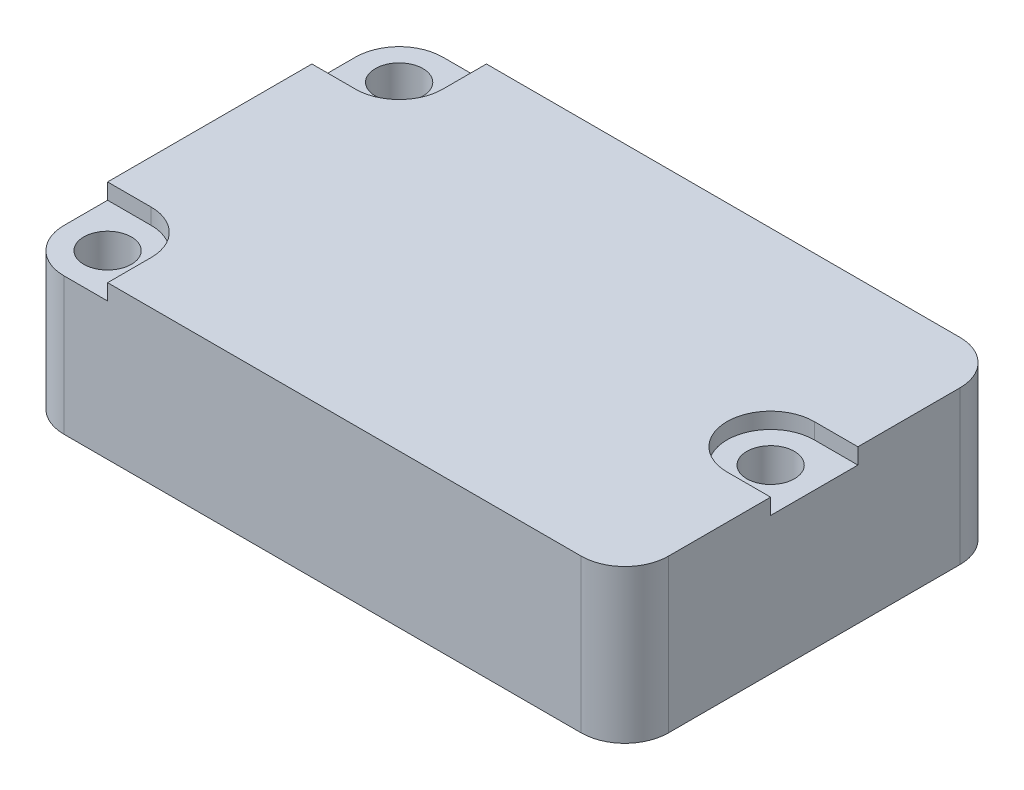
SolidWorks part; units mm, degrees
ref_plane "Front Plane" through (0, 0, 0) normal (0, 0, 1) x (1, 0, 0)
ref_plane "Top Plane" through (0, 0, 0) normal (0, 1, 0) x (1, 0, 0)
ref_plane "Right Plane" through (0, 0, 0) normal (1, 0, 0) x (0, 0, -1)
sketch "Sketch1" plane through (0, 0, 0) normal (0, 1, 0) x (1, 0, 0)
  line L0 (35.35, -2.75) -> (35.35, -21.126) construction
  line L1 (2.75, 0) -> (35.35, 0)
  line L2 (0, -2.75) -> (0, -21.126)
  line L3 (2.75, -23.876) -> (35.35, -23.876)
  line L4 (38.1, -2.75) -> (38.1, -21.126)
  arc A0 (35.35, 0) -> (38.1, -2.75) centre (35.35, -2.75) cw
  arc A1 (35.35, -23.876) -> (38.1, -21.126) centre (35.35, -21.126) ccw
  arc A2 (0, -21.126) -> (2.75, -23.876) centre (2.75, -21.126) ccw
  arc A3 (2.75, 0) -> (0, -2.75) centre (2.75, -2.75) ccw
  circle A4 centre (2.75, -2.75) radius 1.5
  circle A7 centre (2.75, -21.126) radius 1.5
  circle A8 centre (35.35, -11.938) radius 1.5
  point P9 (38.1, -23.876)
  point P12 (0, -23.876)
  point P15 (0, 0)
  dimension "D3" = 2.75
  dimension "D4" = 3
  dimension "D5" = 3
  dimension "D6" = 3
  dimension "D1" = 23.876
  dimension "D2" = 38.1
extrude "Boss-Extrude1" add sketch "Sketch1" along normal blind 9.65
sketch "Sketch2" plane through (0, 9.65, 0) normal (0, 1, 0) x (1, 0, 0)
  line L4 (5.5, -5.5) -> (0, -5.5)
  line L6 (5.5, -5.5) -> (5.5, 0)
  line L7 (5.5, 0) -> (0, 0)
  line L8 (0, -5.5) -> (0, 0)
  line L9 (5.5, -18.376) -> (0, -18.376)
  line L10 (5.5, -18.376) -> (5.5, -23.876)
  line L11 (38.1, -21.126) -> (38.1, -2.75) construction
  line L12 (35.35, -9.188) -> (38.1, -9.188)
  line L13 (35.35, -9.188) -> (35.35, -14.688)
  line L14 (35.35, -14.688) -> (38.1, -14.688)
  line L15 (38.1, -9.188) -> (38.1, -14.688)
  line L16 (5.5, -23.876) -> (0, -23.876)
  line L17 (0, -18.376) -> (0, -23.876)
  circle A0 centre (2.75, -2.75) radius 2.75
  circle A1 centre (2.75, -21.126) radius 2.75
  circle A2 centre (35.35, -11.938) radius 2.75
  line M25 (35.35, 0) -> (2.75, 0)
  arc M26 (2.75, 0) -> (0, -2.75) centre (2.75, -2.75) ccw
  line M27 (0, -2.75) -> (0, -21.126)
  arc M28 (0, -21.126) -> (2.75, -23.876) centre (2.75, -21.126) ccw
  line M29 (2.75, -23.876) -> (35.35, -23.876)
  line M31 (38.1, -21.126) -> (38.1, -2.75)
  circle M32 centre (2.75, -2.75) radius 1.5
  circle M33 centre (35.35, -11.938) radius 1.5
  circle M34 centre (2.75, -21.126) radius 1.5
  dimension "D1" = 5.5
  dimension "D2" = 5.5
  dimension "D3" = 5.5
extrude "Cut-Extrude1" cut sketch "Sketch2" against normal blind 1 contours A1 L9 M27 | L17 L16 M28 | A1 M28 M34 | M34 | A1 L10 M29 | A0 M26 M32 | M32 | A0 L4 M27 | L8 L7 M26 | A0 L6 M25 | L13 A2 M33 | L13 M33 | L13 M33 | L13 A2 M33 | A2 L14 M31 | A2 L15 L12
sketch "Sketch3" plane through (0, 9.65, 0) normal (0, 1, 0) x (1, 0, 0)
  line L0 (29.6, 0) -> (29.6, -23.876) construction
  line L1 (35.35, 0) -> (5.5, 0) construction
  line L2 (5.5, -23.876) -> (35.35, -23.876) construction
  line L3 (38.1, -14.688) -> (29.6, -14.688) construction
  line L4 (38.1, -9.188) -> (38.1, -2.75) construction
  dimension "D1" = 8.5
sketch "Sketch4" plane through (0, 0, 0) normal (-1, 0, 0) x (0, 0, 1)
  line L0 (11.938, 0) -> (11.938, 9.65) construction
  line L1 (2.75, 0) -> (21.126, 0) construction
  line L2 (5.5, 9.65) -> (18.376, 9.65) construction
  line L3 (0, 8.65) -> (0, 0) construction
  line L4 (5.5, 8) -> (18.376, 8)
  line L5 (5.5, 8) -> (5.5, 0)
  line L6 (5.5, 0) -> (18.376, 0)
  line L7 (18.376, 8) -> (18.376, 0)
  line L8 (5.5, 8) -> (18.376, 0) construction
  line L9 (5.5, 0) -> (18.376, 8) construction
  point P6 (11.938, 4)
  dimension "D1" = 5.5
  dimension "D2" = 8
extrude "Cut-Extrude2" cut sketch "Sketch4" against normal blind 3
equation "\"D2@Sketch2\"=\"D1@Sketch2\""
equation "\"D3@Sketch2\"=\"D1@Sketch2\""
